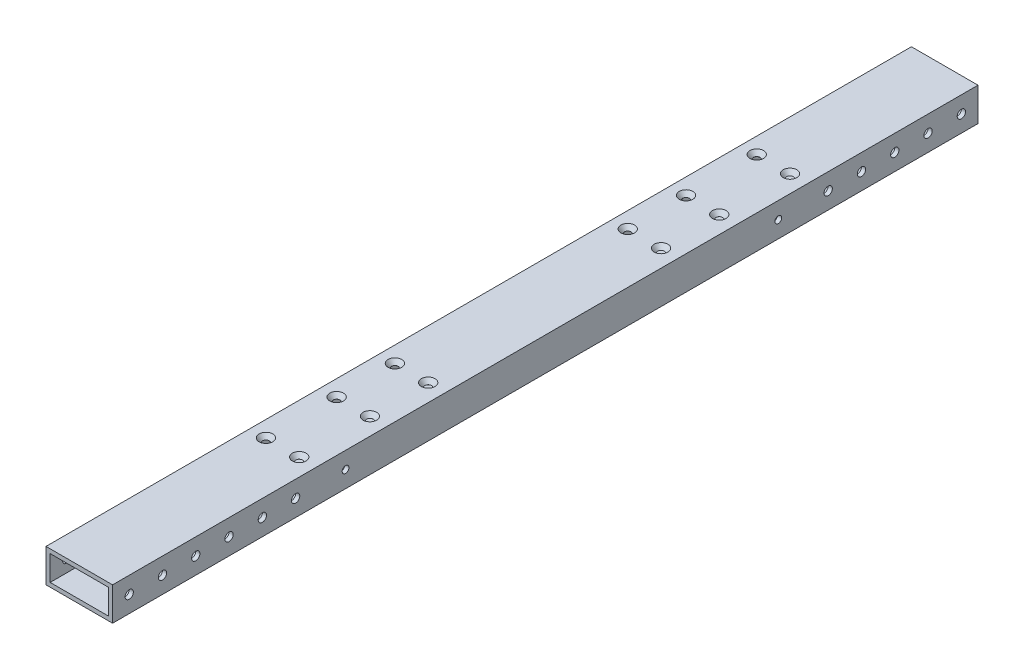
SolidWorks part; units mm, degrees
material "6061 Alloy"
ref_plane "Front Plane" through (0, 0, 0) normal (0, 0, 1) x (1, 0, 0)
ref_plane "Top Plane" through (0, 0, 0) normal (0, 1, 0) x (1, 0, 0)
ref_plane "Right Plane" through (0, 0, 0) normal (1, 0, 0) x (0, 0, -1)
sketch "Sketch1" plane through (0, 0, 0) normal (0, 0, 1) x (1, 0, 0)
  line L0 (-22.225, 9.525) -> (22.225, 9.525)
  line L2 (-25.4, 12.7) -> (25.4, 12.7)
  line L3 (-25.4, 12.7) -> (-25.4, -12.7)
  line L4 (-25.4, -12.7) -> (25.4, -12.7)
  line L5 (25.4, 12.7) -> (25.4, -12.7)
  line L10 (22.225, 9.525) -> (22.225, -9.525)
  line L11 (-22.225, -9.525) -> (22.225, -9.525)
  line L12 (-22.225, 9.525) -> (-22.225, -9.525)
  point P12 (0, 12.7)
  point P14 (25.4, 0)
  dimension "Wall Thickness" = 3.175
  dimension "Outside Width" = 50.8
  dimension "Outside Height" = 25.4
  dimension "Inside Height" = 19.05
  dimension "Inside Width" = 44.45
sketch "Sketch2" plane through (0, 0, 0) normal (1, 0, 0) x (0, 0, -1)
  line L0 (330.2, 0) -> (-330.2, 0)
  point P4 (0, 0)
  point P7 (-330.2, 0)
  point P10 (330.2, 0)
  dimension "Length" = 660.4
sketch "Sketch3" plane through (0, 0, 0) normal (0, 0, 1) x (1, 0, 0)
  line L21 (25.4, 12.7) -> (-25.4, 12.7)
  line L22 (25.4, -12.7) -> (25.4, 12.7)
  line L23 (-25.4, -12.7) -> (25.4, -12.7)
  line L24 (-25.4, 12.7) -> (-25.4, -12.7)
  line L25 (25.4, 12.7) -> (-25.4, 12.7)
  line L26 (25.4, -12.7) -> (25.4, 12.7)
  line L27 (-25.4, -12.7) -> (25.4, -12.7)
  line L28 (-25.4, 12.7) -> (-25.4, -12.7)
  line L29 (22.225, 9.525) -> (-22.225, 9.525)
  line L30 (22.225, -9.525) -> (22.225, 9.525)
  line L31 (-22.225, -9.525) -> (22.225, -9.525)
  line L32 (-22.225, 9.525) -> (-22.225, -9.525)
  line L33 (22.225, 9.525) -> (-22.225, 9.525)
  line L34 (22.225, -9.525) -> (22.225, 9.525)
  line L35 (-22.225, -9.525) -> (22.225, -9.525)
  line L36 (-22.225, 9.525) -> (-22.225, -9.525)
  dimension "D1" = 0
  dimension "D2" = 0
extrude "Boss-Extrude1" add sketch "Sketch3" along normal up to vertex (330.2 mm away) and the other way up to vertex (330.2 mm away) up to point (0, 0, 330.2) other way up to point (0, 0, -330.2)
sketch "Drawing Reference" plane through (0, 0, 0) normal (1, 0, 0) x (0, 0, -1)
  line L0 (-330.2, 0) -> (330.2, 0) construction
  line L1 (0, -12.7) -> (0, 12.7) construction
  line L2 (-330.2, -12.7) -> (330.2, -12.7) construction
  line L5 (-330.2, 12.7) -> (330.2, 12.7) construction
  point P7 (-293.624, 0)
  point P8 (293.624, 0)
  dimension "D1" = 36.576
sketch "Sketch5" plane through (25.4, 0, 0) normal (1, 0, 0) x (0, 0, -1)
  line L2 (-266.7, 0) -> (-241.3, 0)
  line L3 (-241.3, 0) -> (-215.9, 0)
  line L4 (-215.9, 0) -> (-190.5, 0)
  line L5 (-317.5, 0) -> (-330.2, 0)
  line L6 (-330.2, -12.7) -> (-330.2, 12.7) construction
  line L7 (-317.5, 0) -> (-292.1, 0)
  line L8 (-292.1, 0) -> (-266.7, 0)
sketch "Sketch8" plane through (25.4, 0, 0) normal (1, 0, 0) x (0, 0, -1)
  line L0 (330.2, 0) -> (292.1, 0)
  line L1 (330.2, -12.7) -> (330.2, 12.7) construction
  line L2 (292.1, 0) -> (266.7, 0)
  line L3 (266.7, 0) -> (241.3, 0)
  line L4 (241.3, 0) -> (215.9, 0)
  line L5 (330.2, 0) -> (317.5, 0)
hole_wizard "1/4 (0.25) Diameter Hole3" positions "Sketch12" profile "Sketch13" hole size "1/4" standard "ANSI Inch" end condition through all
sketch "Sketch12" plane through (-25.4, 0, 0) normal (-1, 0, 0) x (0, 0, 1)
  point P4 (-317.5, 0)
sketch "Sketch13" plane through (-25.4, 0, -317.5) normal (0, 1, 0) x (0, 0, 1)
  line L0 (0, 0) -> (0, 50.8)
  line L1 (0, 50.8) -> (3.175, 50.8)
  line L2 (3.175, 50.8) -> (3.175, 0)
  line L5 (3.175, 0) -> (0, 0)
  line L11 (0, -6.35) -> (0, 107.95) construction
  dimension "Thru Hole Dia." = 6.35
  dimension "Thru Hole Depth" = 50.8
hole_wizard "1/4 (0.25) Diameter Hole4" positions "Sketch14" profile "Sketch15" hole size "1/4" standard "ANSI Inch" end condition through all
sketch "Sketch14" plane through (-25.4, 0, 0) normal (-1, 0, 0) x (0, 0, 1)
  point P0 (292.1, 0)
  point P3 (317.5, 0)
sketch "Sketch15" plane through (-25.4, 0, 292.1) normal (0, 1, 0) x (0, 0, 1)
  line L0 (0, 0) -> (0, 50.8)
  line L1 (0, 50.8) -> (3.175, 50.8)
  line L2 (3.175, 50.8) -> (3.175, 0)
  line L5 (3.175, 0) -> (0, 0)
  line L11 (0, -6.35) -> (0, 107.95) construction
  dimension "Thru Hole Dia." = 6.35
  dimension "Thru Hole Depth" = 50.8
hole_wizard "1/4 (0.25) Diameter Hole5" positions "Sketch17" profile "Sketch18" hole size "1/4" standard "ANSI Inch" end condition through all
sketch "Sketch17" plane through (25.4, 0, 0) normal (1, 0, 0) x (0, 0, -1)
  point P0 (292.1, 0)
  point P3 (266.7, 0)
sketch "Sketch18" plane through (25.4, 0, -292.1) normal (0, 1, 0) x (0, 0, -1)
  line L0 (0, 0) -> (0, 50.8)
  line L1 (0, 50.8) -> (3.175, 50.8)
  line L2 (3.175, 50.8) -> (3.175, 0)
  line L5 (3.175, 0) -> (0, 0)
  line L11 (0, -6.35) -> (0, 107.95) construction
  dimension "Thru Hole Dia." = 6.35
  dimension "Thru Hole Depth" = 50.8
hole_wizard "1/4 (0.25) Diameter Hole6" positions "Sketch19" profile "Sketch20" hole size "1/4" standard "ANSI Inch" end condition through all
sketch "Sketch19" plane through (25.4, 0, 0) normal (1, 0, 0) x (0, 0, -1)
  point P0 (215.9, 0)
  point P3 (241.3, 0)
sketch "Sketch20" plane through (25.4, 0, -215.9) normal (0, 1, 0) x (0, 0, -1)
  line L0 (0, 0) -> (0, 50.8)
  line L1 (0, 50.8) -> (3.175, 50.8)
  line L2 (3.175, 50.8) -> (3.175, 0)
  line L5 (3.175, 0) -> (0, 0)
  line L11 (0, -6.35) -> (0, 107.95) construction
  dimension "Thru Hole Dia." = 6.35
  dimension "Thru Hole Depth" = 50.8
hole_wizard "1/4 (0.25) Diameter Hole7" positions "Sketch21" profile "Sketch22" hole size "1/4" standard "ANSI Inch" end condition through all
sketch "Sketch21" plane through (25.4, 0, 0) normal (1, 0, 0) x (0, 0, -1)
  point P0 (-190.5, 0)
  point P3 (-215.9, 0)
sketch "Sketch22" plane through (25.4, 0, 190.5) normal (0, 1, 0) x (0, 0, -1)
  line L0 (0, 0) -> (0, 50.8)
  line L1 (0, 50.8) -> (3.175, 50.8)
  line L2 (3.175, 50.8) -> (3.175, 0)
  line L5 (3.175, 0) -> (0, 0)
  line L11 (0, -6.35) -> (0, 107.95) construction
  dimension "Thru Hole Dia." = 6.35
  dimension "Thru Hole Depth" = 50.8
hole_wizard "1/4 (0.25) Diameter Hole8" positions "Sketch23" profile "Sketch24" hole size "1/4" standard "ANSI Inch" end condition through all
sketch "Sketch23" plane through (25.4, 0, 0) normal (1, 0, 0) x (0, 0, -1)
  point P0 (-266.7, 0)
  point P3 (-241.3, 0)
sketch "Sketch24" plane through (25.4, 0, 266.7) normal (0, 1, 0) x (0, 0, -1)
  line L0 (0, 0) -> (0, 50.8)
  line L1 (0, 50.8) -> (3.175, 50.8)
  line L2 (3.175, 50.8) -> (3.175, 0)
  line L5 (3.175, 0) -> (0, 0)
  line L11 (0, -6.35) -> (0, 107.95) construction
  dimension "Thru Hole Dia." = 6.35
  dimension "Thru Hole Depth" = 50.8
sketch "Sketch25" plane through (25.4, 0, 0) normal (1, 0, 0) x (0, 0, -1)
  line L0 (-190.5, 0) -> (-152.4, 0)
  line L1 (215.9, 0) -> (177.8, 0)
hole_wizard "13/64 (0.20313) Diameter Hole1" positions "Sketch26" profile "Sketch27" hole size "13/64" standard "ANSI Inch" end condition through all
sketch "Sketch26" plane through (25.4, 0, 0) normal (1, 0, 0) x (0, 0, -1)
  point P0 (-152.4, 0)
  point P3 (177.8, 0)
sketch "Sketch27" plane through (25.4, 0, 152.4) normal (0, 1, 0) x (0, 0, -1)
  line L0 (0, 0) -> (0, 50.8)
  line L1 (0, 50.8) -> (2.5798, 50.8)
  line L2 (2.5798, 50.8) -> (2.5798, 0)
  line L5 (2.5798, 0) -> (0, 0)
  line L11 (0, -6.35) -> (0, 107.95) construction
  dimension "Thru Hole Dia." = 5.1595
  dimension "Thru Hole Depth" = 50.8
hole_wizard "1/2 (0.5) Diameter Hole1" positions "Sketch33" profile "Sketch34" hole size "1/2" standard "ANSI Inch"
sketch "Sketch33" plane through (-25.4, 0, 0) normal (-1, 0, 0) x (0, 0, 1)
  point P0 (-146.05, 0)
  point P3 (120.65, 0)
sketch "Sketch34" plane through (-25.4, 0, -146.05) normal (0, 1, 0) x (0, 0, 1)
  line L0 (0, 0) -> (0, 10.1655)
  line L1 (0, 10.1655) -> (6.35, 6.35)
  line L2 (6.35, 6.35) -> (6.35, 0)
  line L5 (6.35, 0) -> (0, 0)
  line L10 (0, 10.1655) -> (-6.35, 6.35) construction
  line L11 (0, -6.35) -> (0, 107.95) construction
  dimension "Hole Dia." = 12.7
  dimension "Hole Depth" = 6.35
  dimension "Drill Angle" = 118
sketch "Sketch35" plane through (0, -12.7, 0) normal (0, -1, 0) x (1, 0, 0)
  line L0 (12.192, -101.5498) -> (-13.208, -101.5498) construction
  line L1 (12.192, 120.5998) -> (-13.208, 120.5998) construction
  line L2 (-13.208, 120.5998) -> (-13.208, 76.1498) construction
  line L3 (-13.208, 76.1498) -> (12.192, 76.1498) construction
  line L4 (12.192, 76.1498) -> (12.192, 120.5998) construction
  line L5 (-13.208, -101.5498) -> (-13.208, -145.9998) construction
  line L6 (-13.208, -145.9998) -> (12.192, -145.9998) construction
  line L7 (12.192, -145.9998) -> (12.192, -101.5498) construction
  line L8 (12.192, 120.5998) -> (12.192, 174.5748) construction
  line L9 (12.192, 174.5748) -> (-13.208, 174.5748) construction
  line L10 (12.192, -145.9998) -> (12.192, -199.9748) construction
  line L11 (12.192, -199.9748) -> (-13.208, -199.9748) construction
hole_wizard "#10 Clearance Hole1" positions "Sketch39" profile "Sketch40" hole size "#10" standard "ANSI Inch" end condition through all
sketch "Sketch39" plane through (0, -12.7, 0) normal (0, -1, 0) x (-1, 0, 0)
  point P0 (13.208, 145.9998)
  point P3 (-12.192, 145.9998)
  point P6 (-12.192, 101.5498)
  point P9 (13.208, 101.5498)
  point P12 (-12.192, -76.1498)
  point P15 (13.208, -76.1498)
  point P18 (13.208, -120.5998)
  point P21 (-12.192, -120.5998)
  point P24 (-12.192, 199.9748)
  point P27 (13.208, 199.9748)
  point P30 (-12.192, -174.5748)
  point P33 (13.208, -174.5748)
sketch "Sketch40" plane through (-13.208, -12.7, -145.9998) normal (1, 0, 0) x (0, 0, -1)
  line L0 (0, 0) -> (0, 25.4)
  line L1 (0, 25.4) -> (5.2197, 25.4)
  line L2 (2.4892, 22.2589) -> (2.4892, 0)
  line L5 (2.4892, 0) -> (0, 0)
  line L7 (5.2197, 25.4) -> (2.4892, 22.2589)
  line L8 (-5.2197, 25.4) -> (-2.4892, 22.2589) construction
  line L11 (0, -6.35) -> (0, 107.95) construction
  dimension "Thru Hole Dia." = 4.9784
  dimension "Thru Hole Depth" = 25.4
  dimension "Far C'Sink Dia." = 10.4394
  dimension "Far C'Sink Angle" = 82
equation "\"D1@Drawing Reference\"=\"Outside Width@Sketch1\" * 0.72"
